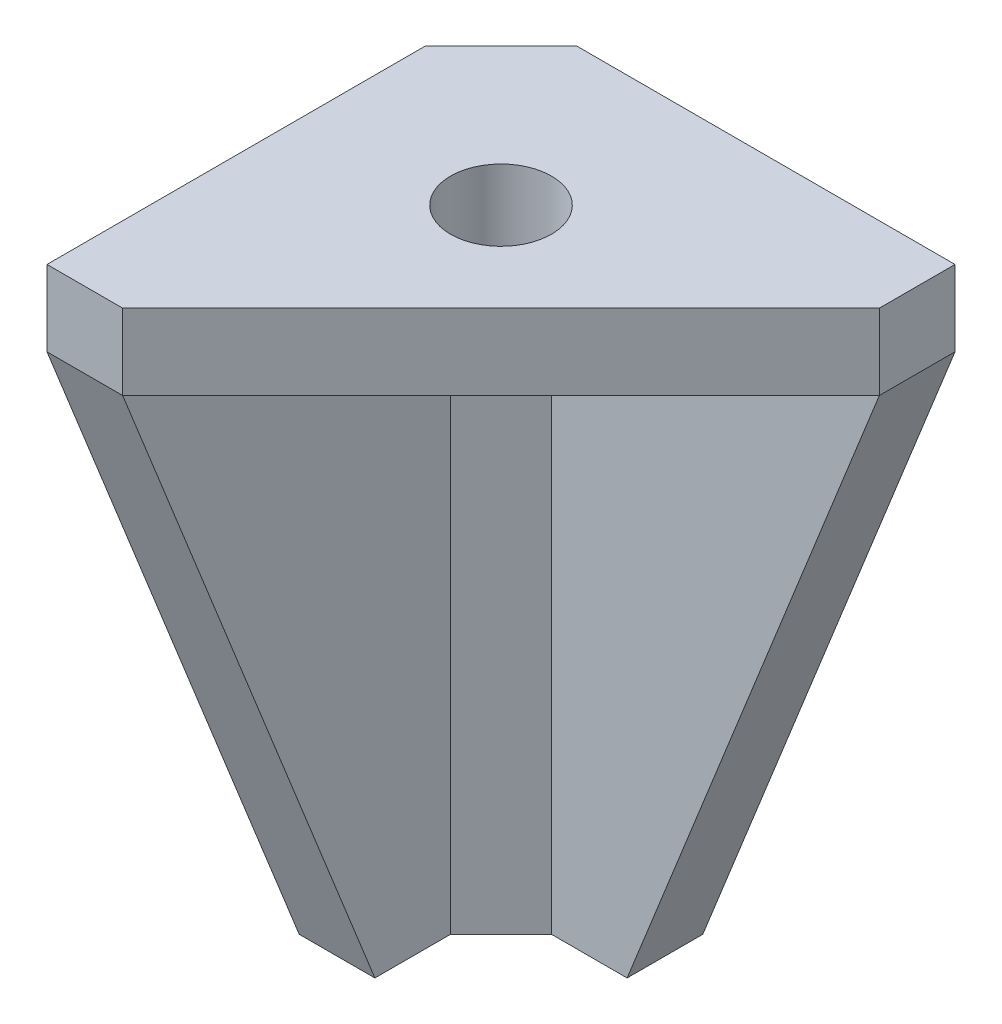
SolidWorks part; units mm, degrees
material "ABS PC"
ref_plane "Front Plane" through (0, 0, 0) normal (0, 0, 1) x (1, 0, 0)
ref_plane "Top Plane" through (0, 0, 0) normal (0, 1, 0) x (1, 0, 0)
ref_plane "Right Plane" through (0, 0, 0) normal (1, 0, 0) x (0, 0, -1)
sketch "Sketch1" plane through (0, 0, 0) normal (0, 0, 1) x (1, 0, 0)
  line L0 (-2.5, 12.5) -> (-2.5, -12.5)
  line L1 (-2.5, -12.5) -> (2.5, -12.5)
  line L2 (2.5, -12.5) -> (12.5, 12.5)
  line L3 (12.5, 12.5) -> (-2.5, 12.5)
  line L4 (-2.5, 12.5) -> (2.5, -12.5) construction
  dimension "D1" = 25
  dimension "D2" = 15
  dimension "D3" = 5
extrude "Boss-Extrude1" add sketch "Sketch1" along normal blind 3
ref_plane "Plane1" through (-2.75, 0, 2.75) normal (-0.7071, 0, 0.7071) x (0, -1, 0)
mirror "Mirror3" about plane through (-2.75, 0, 2.75) normal (-0.7071, 0, 0.7071) of bodies 101
sketch "Sketch3" plane through (0, 12.5, 0) normal (0, 1, 0) x (1, 0, 0)
  line L0 (-5.5, -3) -> (-2.5, 0)
  line L1 (-2.5, 0) -> (-2.5, -3)
  line L2 (-2.5, -3) -> (-5.5, -3)
extrude "Boss-Extrude2" add sketch "Sketch3" against normal through all
sketch "Sketch5" plane through (0, 12.5, 0) normal (0, 1, 0) x (1, 0, 0)
  line L15 (-2.5, -18) -> (12.5, -3)
  line L20 (-5.5, -18) -> (-2.5, -18)
  line L21 (12.5, -3) -> (12.5, 0)
  line L22 (12.5, 0) -> (-2.5, 0)
  line L23 (-2.5, 0) -> (-5.5, -3)
  line L24 (-5.5, -3) -> (-5.5, -18)
  line L25 (-5.5, -18) -> (-2.5, -18)
  line L26 (12.5, -3) -> (12.5, 0)
  line L27 (12.5, 0) -> (-2.5, 0)
  line L28 (-2.5, 0) -> (-5.5, -3)
  line L29 (-5.5, -3) -> (-5.5, -18)
  dimension "D1" = 0
extrude "Boss-Extrude3" add sketch "Sketch5" along normal blind 3
hole_wizard "Ø4.0 (4) Diameter Hole1" positions "Sketch7" profile "Sketch8" hole size "Ø4.0" standard "ANSI Metric" end condition through all
sketch "Sketch7" plane through (0, 15.5, 0) normal (0, 1, 0) x (1, 0, 0)
  line L0 (5, -10.5) -> (1.4645, -6.9645) construction
  line L1 (-2.5, -18) -> (12.5, -3) construction
  point P1 (1.4645, -6.9645)
  point P7 (7.5, -17.5)
  dimension "D1" = 5
sketch "Sketch8" plane through (1.4645, 15.5, 6.9645) normal (1, 0, 0) x (0, 0, 1)
  line L0 (0, 0) -> (0, 28)
  line L1 (0, 28) -> (2, 28)
  line L2 (2, 28) -> (2, 0)
  line L5 (2, 0) -> (0, 0)
  line L11 (0, -6.35) -> (0, 107.95) construction
  dimension "Thru Hole Dia." = 4
  dimension "Thru Hole Depth" = 28
chamfer "Chamfer2" distance 2 angle 45 1 edges at (-2.5, 0, 3)
